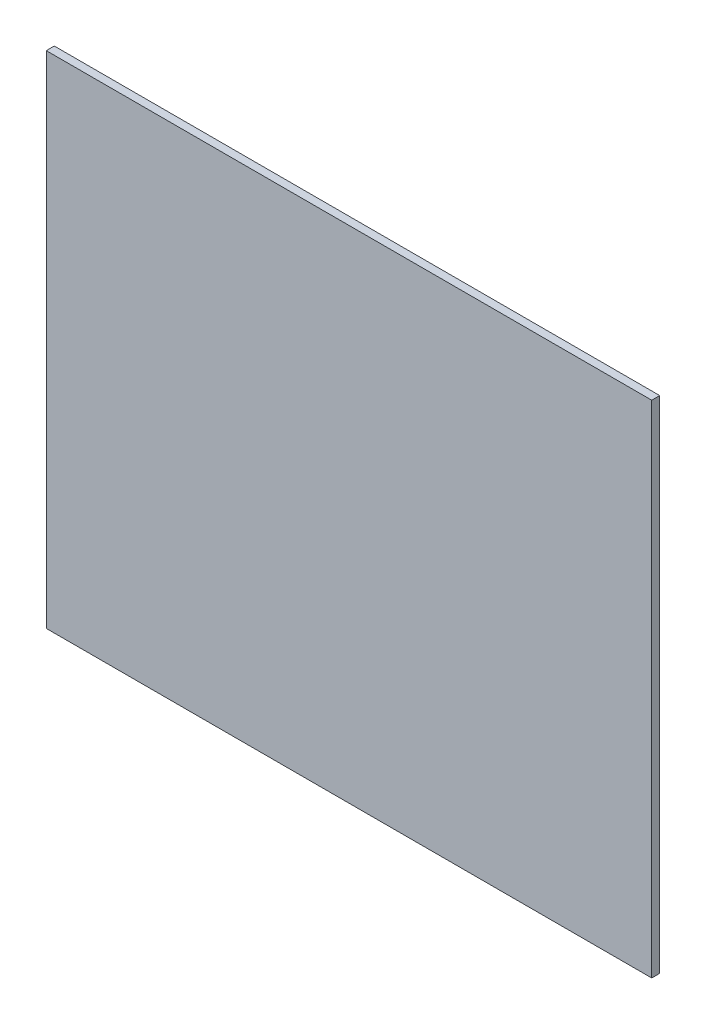
SolidWorks part; units mm, degrees
ref_plane "Front Plane" through (0, 0, 0) normal (0, 0, 1) x (1, 0, 0)
ref_plane "Top Plane" through (0, 0, 0) normal (0, 1, 0) x (1, 0, 0)
ref_plane "Right Plane" through (0, 0, 0) normal (1, 0, 0) x (0, 0, -1)
sketch "Sketch1" plane through (0, 0, 0) normal (0, 0, 1) x (1, 0, 0)
  line L1 (-48.7088, 16.5) -> (11.7912, 16.5)
  line L2 (-48.7088, 16.5) -> (-48.7088, -33.5)
  line L3 (-48.7088, -33.5) -> (11.7912, -33.5)
  line L4 (11.7912, 16.5) -> (11.7912, -33.5)
  dimension "D1" = 50
  dimension "D2" = 60.5
extrude "Boss-Extrude1" add sketch "Sketch1" along normal blind 0.8
